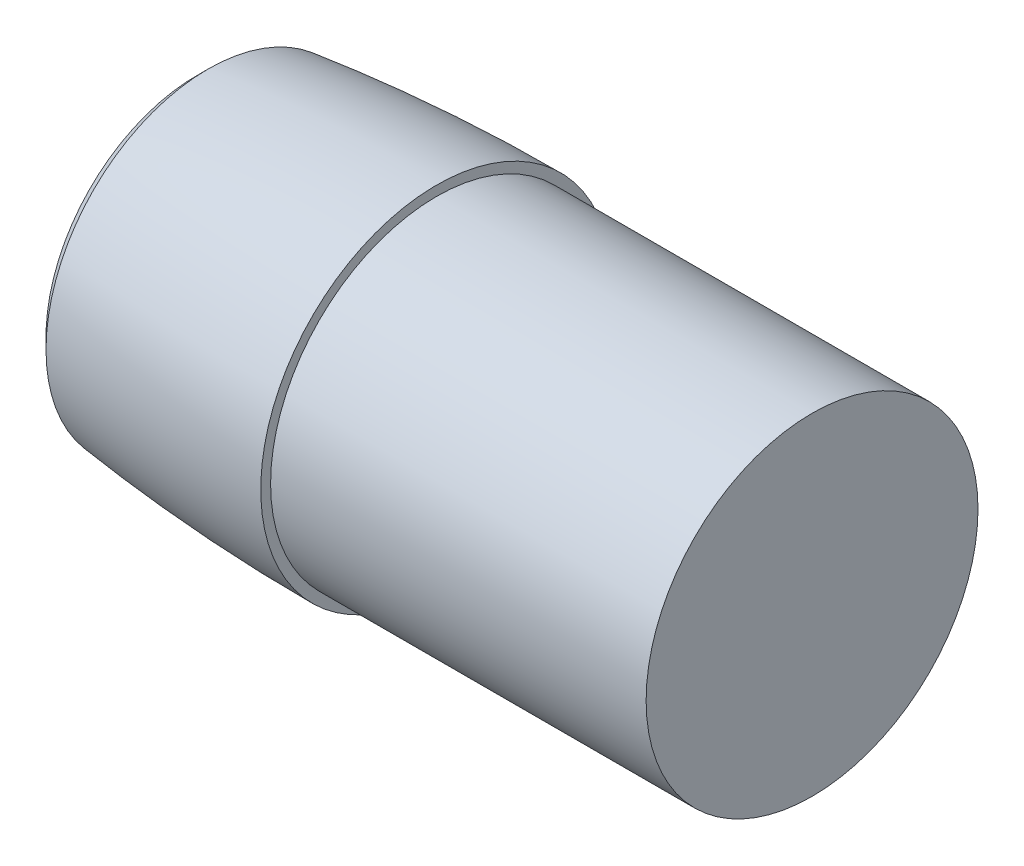
SolidWorks part; units mm, degrees
ref_plane "Front Plane" through (0, 0, 0) normal (0, 0, 1) x (1, 0, 0)
ref_plane "Top Plane" through (0, 0, 0) normal (0, 1, 0) x (1, 0, 0)
ref_plane "Right Plane" through (0, 0, 0) normal (1, 0, 0) x (0, 0, -1)
sketch "Sketch2" plane through (0, 0, 0) normal (0, 0, 1) x (1, 0, 0)
  line L0 (-0.0615, 438.4881) -> (-0.0615, 436.2381) construction
  line L1 (-0.0615, 438.4881) -> (-0.0615, 436.2381)
  line L3 (-0.0615, 436.2381) -> (85.9385, 436.2381)
  line L4 (85.9385, 436.2381) -> (85.9385, 398.2381)
  line L6 (85.9385, 398.2381) -> (80.9385, 398.2381)
  line L7 (-5.0615, 436.2381) -> (-5.0615, 431.2381)
  line L8 (-5.0615, 431.2381) -> (80.9385, 431.2381)
  line L12 (-0.0615, 403.2381) -> (-166.5183, 403.2381) construction
  line L13 (-0.0615, 398.2381) -> (-190.0615, 398.2381) construction
  line L16 (80.9385, 403.2381) -> (-0.0615, 403.2381) construction
  line L17 (85.9385, 398.2381) -> (-0.0615, 398.2381) construction
  line L18 (80.9385, 398.2381) -> (80.9385, 431.2381)
  line L19 (80.9385, 431.2381) -> (80.9385, 403.2381) construction
  line L20 (-190.0615, 398.2381) -> (-231.9833, 398.2381) construction
  line L21 (80.9385, 398.2381) -> (85.9385, 398.2381) construction
  line L23 (-52.3806, 435.3482) -> (-54.9338, 432.7951)
  line L24 (-0.0615, 441.2674) -> (-0.0615, 436.2381) construction
  line L25 (-54.9338, 432.7951) -> (-54.9338, 435.6744) construction
  arc A3 (-5.0615, 436.2381) -> (-166.5183, 403.2381) centre (0, 0) ccw construction
  arc A5 (-5.0615, 436.2381) -> (-54.9338, 432.7951) centre (0, 0) ccw
  arc A6 (80.9385, 430.9533) -> (79.4073, 431.2381) centre (0, 0) ccw
  arc A7 (-0.0615, 441.2674) -> (-190.0615, 398.2381) centre (0, 0) ccw construction
  arc A8 (-0.0615, 438.4881) -> (-52.0319, 435.39) centre (0, 0) ccw
  arc A11 (-0.0615, 438.4881) -> (-52.3806, 435.3482) centre (0, 0) ccw construction
  arc A12 (-0.0615, 438.4881) -> (-52.3806, 435.3482) centre (0, 0) ccw
  arc A13 (80.9385, 430.9533) -> (79.4073, 431.2381) centre (0, 0) ccw construction
  arc A14 (80.9385, 430.9533) -> (79.4073, 431.2381) centre (0, 0) ccw
  dimension "D1" = 49.8722
  dimension "D10" = 38
  dimension "D3" = 86
  dimension "D4" = 2.25
  dimension "D5" = 5
  dimension "D6" = 135.1278
  dimension "D7" = 276
  dimension "D8" = 5
  dimension "D9" = 45
revolve "Revolve1" add sketch "Sketch2" angle 360 about L20
